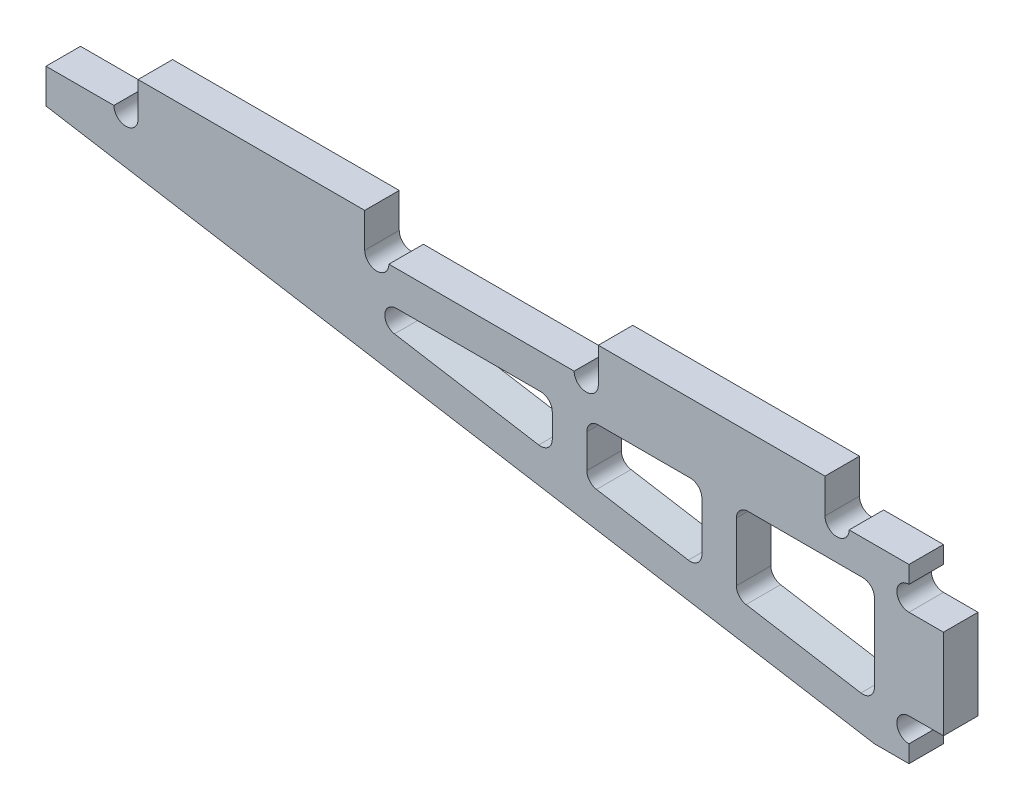
SolidWorks part; units mm, degrees
material "Thornel Mat VMA"
ref_plane "前视基准面" through (0, 0, 0) normal (0, 0, 1) x (1, 0, 0)
ref_plane "上视基准面" through (0, 0, 0) normal (0, 1, 0) x (1, 0, 0)
ref_plane "右视基准面" through (0, 0, 0) normal (1, 0, 0) x (0, 0, -1)
sketch "草图1" plane through (0, 0, 0) normal (0, 0, 1) x (1, 0, 0)
  line L0 (-9.85, -1.5) -> (-30.15, -1.5)
  line L1 (9.85, -1.5) -> (-9.85, -1.5) construction
  line L2 (9.85, -1.5) -> (9.85, 1.5)
  line L3 (9.85, 1.5) -> (-9.85, 1.5)
  line L4 (-9.85, -1.5) -> (-9.85, 1.5)
  line L5 (9.85, -1.5) -> (-9.85, 1.5) construction
  line L6 (9.85, 1.5) -> (-9.85, -1.5) construction
  line L7 (-30.15, -1.5) -> (-30.15, 1.5)
  line L8 (-30.15, 1.5) -> (-49.85, 1.5)
  line L9 (-49.85, 1.5) -> (-49.85, -1.5)
  line L10 (-49.85, -1.5) -> (-57.85, -1.5)
  line L11 (9.85, -1.5) -> (17.15, -1.5)
  line L12 (17.15, -1.5) -> (17.15, -5.1)
  line L13 (17.15, -5.1) -> (20.15, -5.1)
  line L14 (20.15, -5.1) -> (20.15, -12.9)
  line L15 (20.15, -12.9) -> (17.15, -12.9)
  line L16 (17.15, -12.9) -> (17.15, -16.5)
  line L17 (17.15, -16.5) -> (14.15, -16.5)
  line L18 (14.15, -16.5) -> (-57.85, -4.5)
  line L19 (-57.85, -4.5) -> (-57.85, -1.5)
  line L20 (-40, 1.5) -> (-40, -0.6585) construction
  line L21 (20.15, -9) -> (18.2799, -9) construction
  line L22 (-39.6017, -4.5) -> (-13.85, -4.5)
  line L23 (14.15, -4.5) -> (14.15, -13.4586)
  line L24 (14.15, -13.4586) -> (2.15, -11.4586)
  line L25 (-13.85, -4.5) -> (-13.85, -8.792)
  line L26 (-10.85, -4.5) -> (-10.85, -9.292)
  line L27 (-10.85, -4.5) -> (-0.85, -4.5)
  line L28 (-13.85, -8.792) -> (-39.6017, -4.5)
  line L29 (-0.85, -4.5) -> (-0.85, -10.9586)
  line L30 (2.15, -4.5) -> (2.15, -11.4586)
  line L31 (2.15, -4.5) -> (14.15, -4.5)
  line L32 (-0.85, -10.9586) -> (-10.85, -9.292)
  circle A0 centre (-50.9, -1.5) radius 1.05
  circle A1 centre (-29.1, -1.5) radius 1.05
  circle A2 centre (-10.9, -1.5) radius 1.05
  circle A3 centre (10.9, -1.5) radius 1.05
  circle A4 centre (17.15, -4.05) radius 1.05
  circle A5 centre (17.15, -13.95) radius 1.05
  point P0 (0, 0)
  dimension "D10" = 2.1
  dimension "D1" = 7.3
  dimension "D2" = 40
  dimension "D3" = 19.7
  dimension "D4" = 3
  dimension "D5" = 8
  dimension "D6" = 3
  dimension "D7" = 7.5
  dimension "D8" = 7.8
  dimension "D9" = 3
  dimension "D11" = 3
  dimension "D12" = 3
  dimension "D13" = 3
  dimension "D14" = 3
  dimension "D15" = 4
  dimension "D16" = 3
  dimension "D17" = 10
extrude "凸台-拉伸1" add sketch "草图1" along normal blind 3 contours A5 L15 L14 L13 A4 L12 L11 A3 L2 L3 L4 A2 L0 A1 L7 L8 L9 A0 L10 L19 L18 L17 L16
fillet "圆角1" radius 1.01 11 edges at (-13.85, -8.792, 1.5) (14.15, -13.4586, 1.5) (-10.85, -4.5, 1.5) (-13.85, -4.5, 1.5) (-39.6017, -4.5, 1.5) (2.15, -11.4586, 1.5) (2.15, -4.5, 1.5) (14.15, -4.5, 1.5) (-0.85, -4.5, 1.5) (-0.85, -10.9586, 1.5) (-10.85, -9.292, 1.5)
